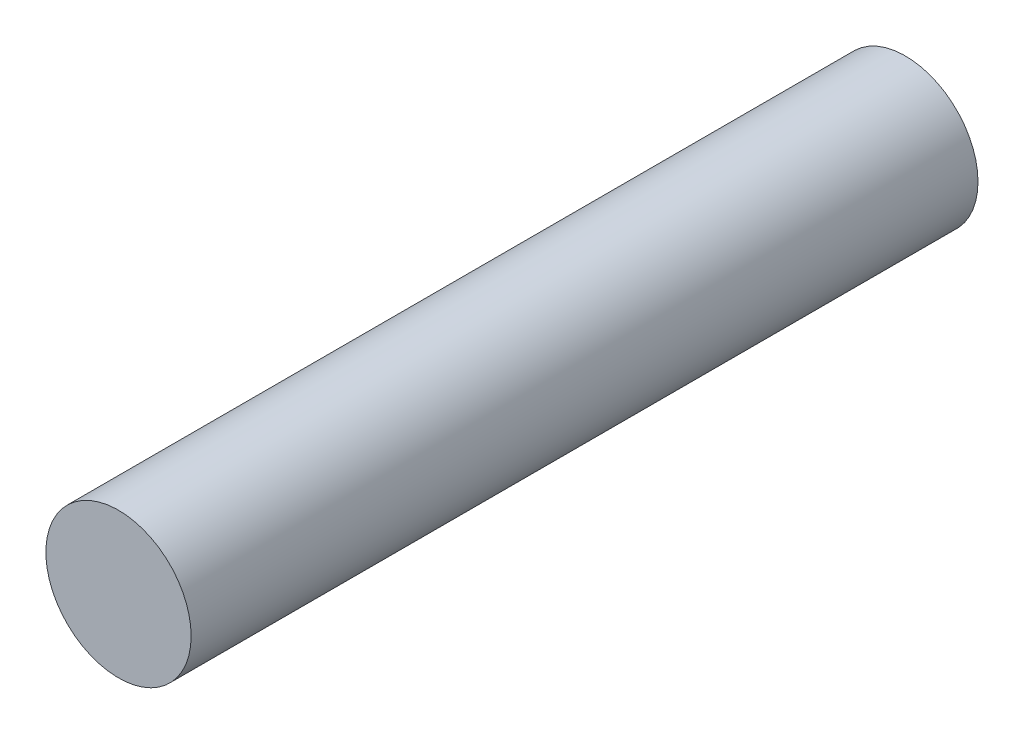
SolidWorks part; units mm, degrees
ref_plane "Front Plane" through (0, 0, 0) normal (0, 0, 1) x (1, 0, 0)
ref_plane "Top Plane" through (0, 0, 0) normal (0, 1, 0) x (1, 0, 0)
ref_plane "Right Plane" through (0, 0, 0) normal (1, 0, 0) x (0, 0, -1)
sketch "Sketch2" plane through (0, 0, 0) normal (0, 0, 1) x (1, 0, 0)
  circle A0 centre (0, 0) radius 6
extrude "Boss-Extrude2" add sketch "Sketch2" along normal blind 65
